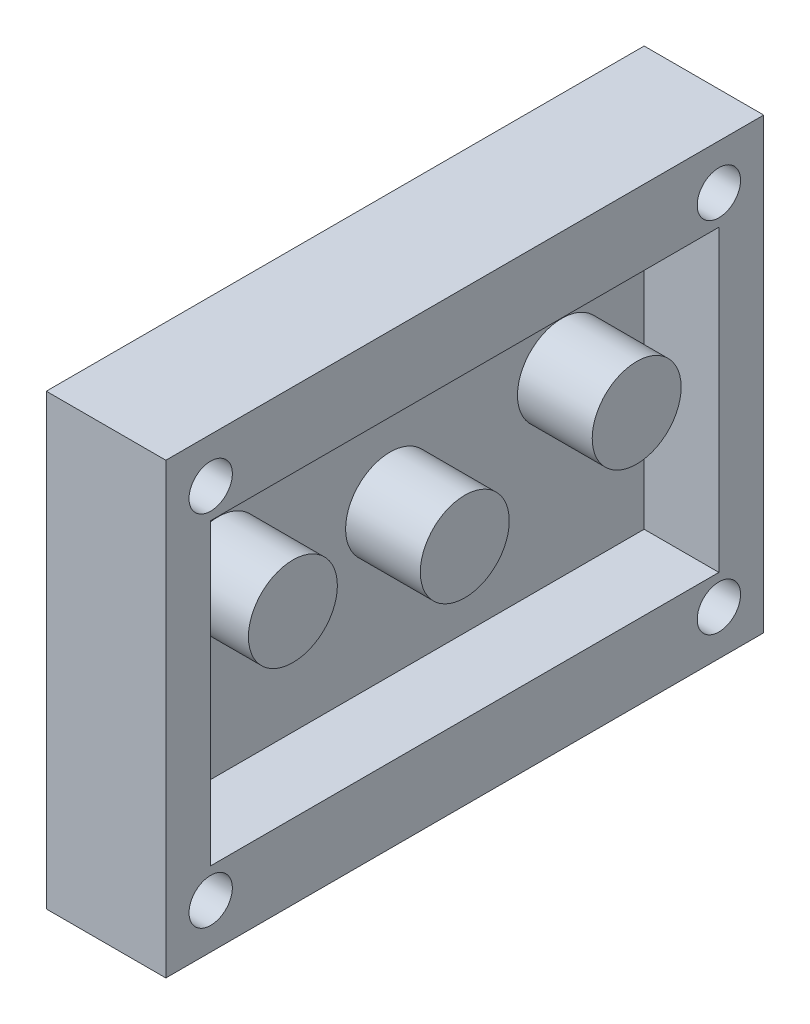
SolidWorks part; units mm, degrees
ref_plane "Front Plane" through (0, 0, 0) normal (0, 0, 1) x (1, 0, 0)
ref_plane "Top Plane" through (0, 0, 0) normal (0, 1, 0) x (1, 0, 0)
ref_plane "Right Plane" through (0, 0, 0) normal (1, 0, 0) x (0, 0, -1)
sketch "Sketch1" plane through (0, 0, 0) normal (1, 0, 0) x (0, 0, -1)
  line L1 (0, 0) -> (40, 0)
  line L2 (0, 0) -> (0, 30)
  line L3 (0, 30) -> (40, 30)
  line L7 (40, 30) -> (40, 0)
  dimension "D1" = 40
  dimension "D2" = 30
extrude "Boss-Extrude1" add sketch "Sketch1" along normal blind 8
sketch "Sketch4" plane through (8, 0, 0) normal (1, 0, 0) x (0, 0, -1)
  line L0 (0, 15) -> (40, 15) construction
  line L1 (0, 30) -> (0, 0) construction
  line L2 (40, 0) -> (40, 30) construction
  line L3 (20, 30) -> (20, 0) construction
  line L4 (40, 30) -> (0, 30) construction
  line L5 (0, 0) -> (40, 0) construction
  line L6 (0, 27) -> (40, 27) construction
  line L7 (3, 5) -> (37, 5)
  line L8 (3, 5) -> (3, 25)
  line L9 (3, 25) -> (37, 25)
  line L10 (37, 5) -> (37, 25)
  line L11 (3, 5) -> (37, 25) construction
  line L12 (3, 25) -> (37, 5) construction
  line L13 (3, 30) -> (3, 0) construction
  line L14 (0, 3) -> (40, 3) construction
  line L15 (37, 30) -> (37, 0) construction
  circle A0 centre (37, 27) radius 1.45
  circle A1 centre (3, 27) radius 1.45
  circle A2 centre (3, 3) radius 1.45
  circle A3 centre (37, 3) radius 1.45
  point P12 (20, 15)
  dimension "D5" = 2.9
  dimension "D1" = 5
  dimension "D2" = 3
  dimension "D3" = 3
  dimension "D4" = 3
extrude "Cut-Extrude1" cut sketch "Sketch4" against normal blind 5
sketch "Sketch5" plane through (3, 0, 0) normal (1, 0, 0) x (0, 0, -1)
  line L0 (3, 15) -> (37, 15) construction
  line L1 (3, 25) -> (3, 5) construction
  line L2 (37, 5) -> (37, 25) construction
  line L3 (3, 17) -> (37, 17) construction
  line L4 (3, 25) -> (3, 5) construction
  line L5 (37, 5) -> (37, 25) construction
  line L6 (3, 13) -> (37, 13) construction
  circle A0 centre (8.5, 17) radius 2.975
  circle A1 centre (20, 15) radius 2.975
  circle A2 centre (31.5, 17) radius 2.975
  dimension "D2" = 5.95
  dimension "D3" = 5.5
  dimension "D1" = 2
  dimension "2mm" = 2
  dimension "D4" = 5.5
extrude "Boss-Extrude2" add sketch "Sketch5" along normal blind 5
